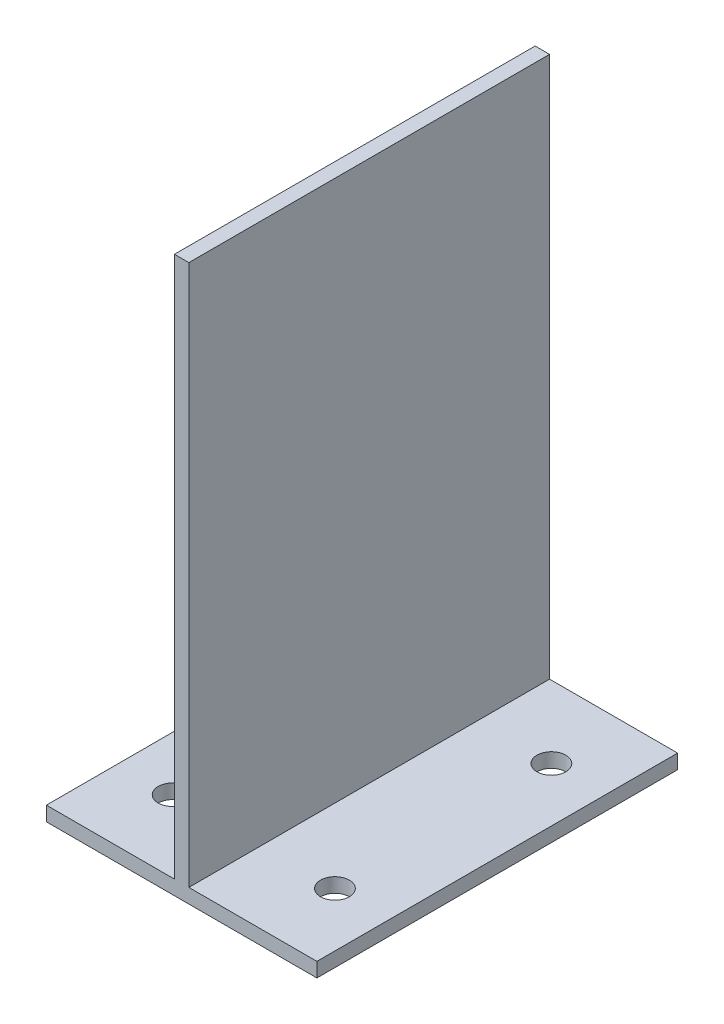
SolidWorks part; units mm, degrees
ref_plane "Front Plane" through (0, 0, 0) normal (0, 0, 1) x (1, 0, 0)
ref_plane "Top Plane" through (0, 0, 0) normal (0, 1, 0) x (1, 0, 0)
ref_plane "Right Plane" through (0, 0, 0) normal (1, 0, 0) x (0, 0, -1)
sketch "Sketch1" plane through (0, 0, 0) normal (0, 0, 1) x (1, 0, 0)
  line L0 (-4, 308) -> (-4, 8)
  line L1 (-4, 8) -> (-75, 8)
  line L2 (-75, 8) -> (-75, 0)
  line L3 (-75, 0) -> (75, 0)
  line L4 (75, 0) -> (75, 8)
  line L5 (75, 8) -> (4, 8)
  line L6 (4, 8) -> (4, 308)
  line L7 (4, 308) -> (-4, 308)
  point P2 (0, 308)
  dimension "D1" = 150
  dimension "D2" = 8
  dimension "D3" = 8
  dimension "D4" = 300
extrude "Boss-Extrude1" add sketch "Sketch1" along normal blind 200
hole_wizard "Ø16.0 mm Dowel Holes1" positions "Sketch2" profile "Sketch3" hole size "Ø16.0" standard "ISO" end condition through all
sketch "Sketch2" plane through (0, 0, 0) normal (0, -1, 0) x (-1, 0, 0)
  line L0 (0, 0) -> (0, -200) construction
  line L1 (75, -200) -> (-75, -200) construction
  line L2 (-45, -160) -> (45, -160) construction
  line L3 (45, -160) -> (45, -40) construction
  line L4 (45, -40) -> (-45, -40) construction
  line L5 (-45, -40) -> (-45, -160) construction
  line L6 (75, -100) -> (-75, -100) construction
  line L7 (75, -200) -> (75, 0) construction
  line L8 (-75, -200) -> (-75, 0) construction
  point P0 (-45, -40)
  point P2 (-45, -160)
  point P4 (45, -160)
  point P6 (45, -40)
  point P26 (0, -40)
  point P35 (45, -100)
  point P36 (0, 0)
  point P38 (69.5929, -40)
  dimension "D1" = 90
  dimension "D2" = 120
sketch "Sketch3" plane through (45, 0, 40) normal (1, 0, 0) x (0, 0, -1)
  line L0 (0, 0) -> (0, 308)
  line L1 (0, 308) -> (8, 308)
  line L2 (8, 308) -> (8, 0)
  line L5 (8, 0) -> (0, 0)
  line L11 (0, -6.35) -> (0, 107.95) construction
  dimension "Thru Hole Dia." = 16
  dimension "Thru Hole Depth" = 308
